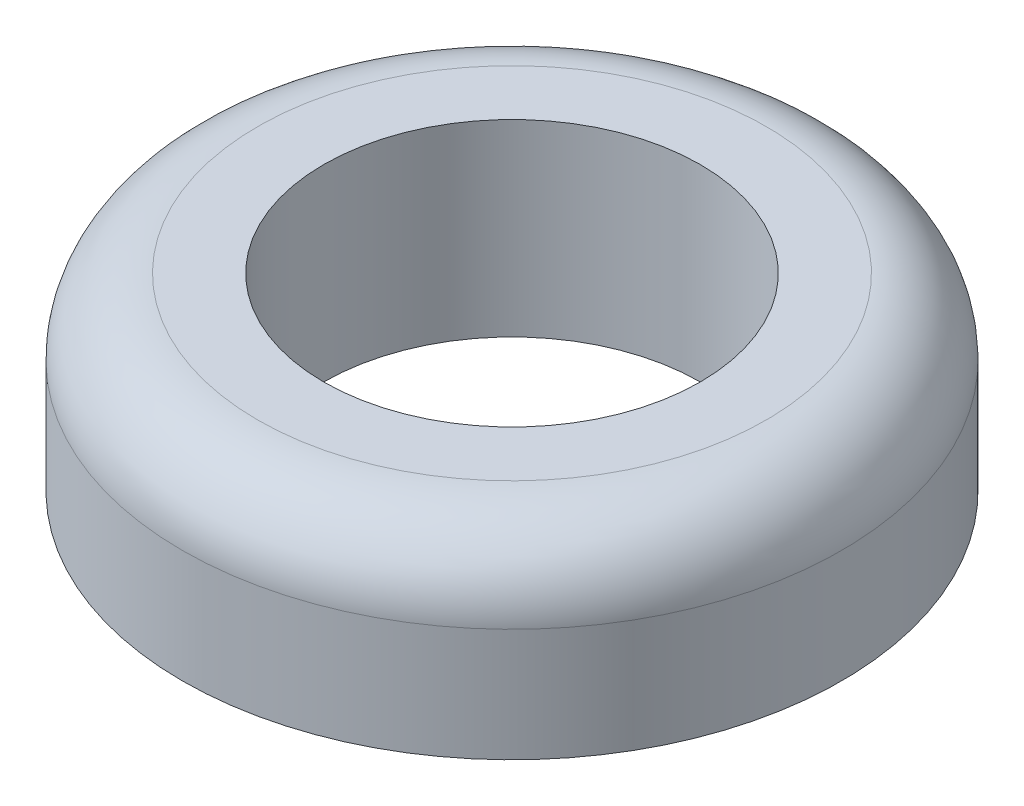
SolidWorks part; units mm, degrees
ref_plane "Front Plane" through (0, 0, 0) normal (0, 0, 1) x (1, 0, 0)
ref_plane "Top Plane" through (0, 0, 0) normal (0, 1, 0) x (1, 0, 0)
ref_plane "Right Plane" through (0, 0, 0) normal (1, 0, 0) x (0, 0, -1)
sketch "Sketch1" plane through (0, 0, 0) normal (0, 1, 0) x (1, 0, 0)
  circle A0 centre (0, 0) radius 1
  circle A1 centre (0, 0) radius 1.75
  dimension "D1" = 2
  dimension "D2" = 3.5
extrude "Boss-Extrude1" add sketch "Sketch1" along normal blind 1
fillet "Fillet1" radius 0.4 1 edges at (0, 1, 1.75)
